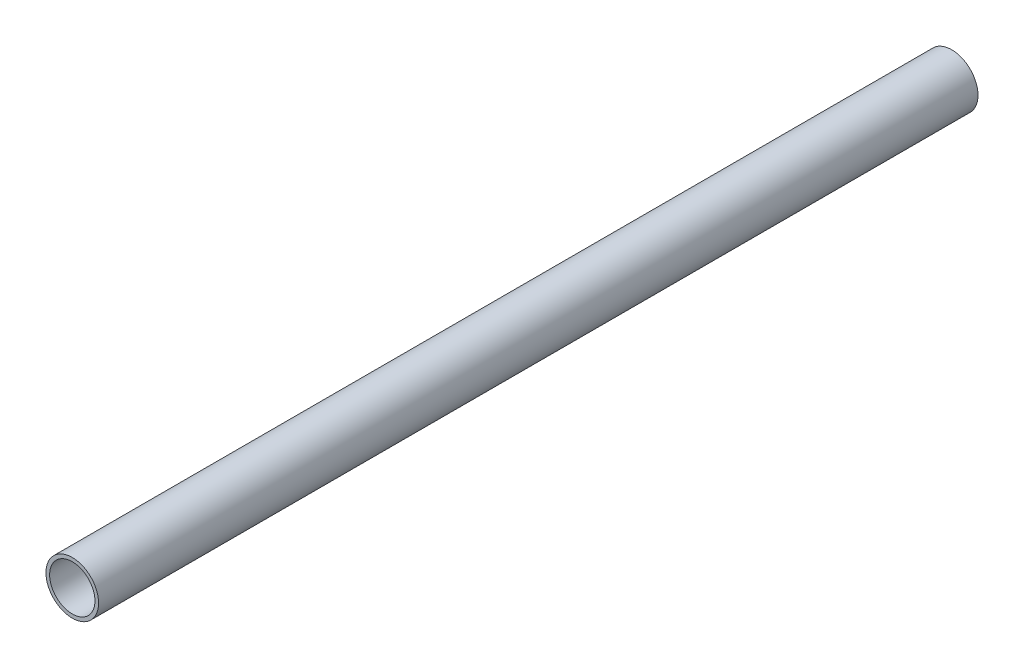
SolidWorks part; units mm, degrees
ref_plane "前视基准面" through (0, 0, 0) normal (0, 0, 1) x (1, 0, 0)
ref_plane "上视基准面" through (0, 0, 0) normal (0, 1, 0) x (1, 0, 0)
ref_plane "右视基准面" through (0, 0, 0) normal (1, 0, 0) x (0, 0, -1)
sketch "草图1" plane through (0, 0, 0) normal (0, 0, 1) x (1, 0, 0)
  circle A0 centre (0, 0) radius 7.55
  circle A1 centre (0, 0) radius 6.5
  dimension "D1" = 15.1
  dimension "D2" = 13
extrude "凸台-拉伸1" add sketch "草图1" along normal blind 252.3
